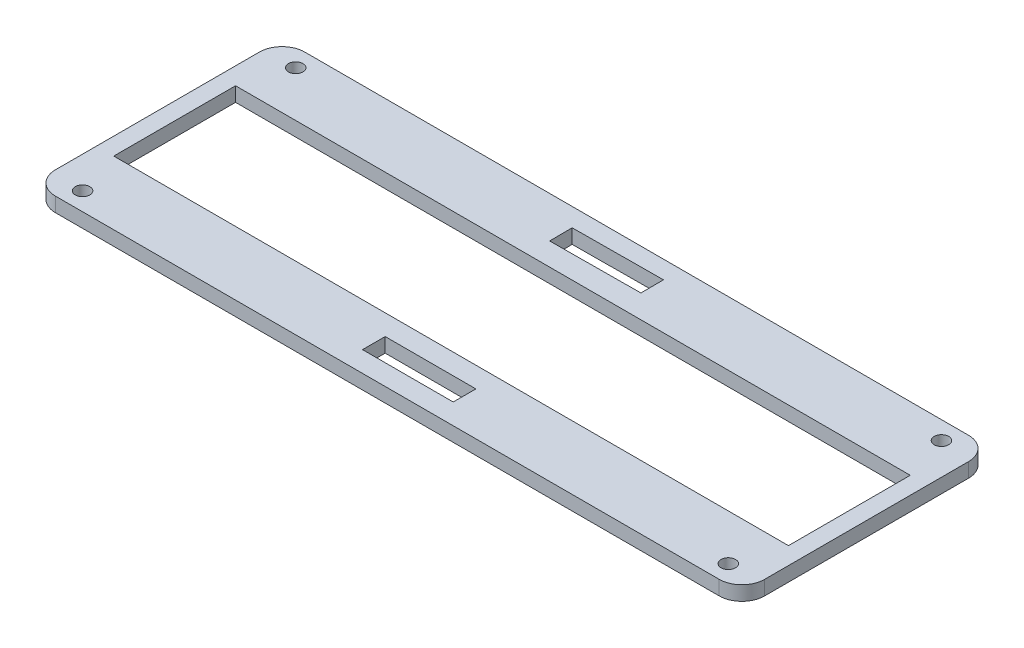
SolidWorks part; units mm, degrees
ref_plane "Front Plane" through (0, 0, 0) normal (0, 0, 1) x (1, 0, 0)
ref_plane "Top Plane" through (0, 0, 0) normal (0, 1, 0) x (1, 0, 0)
ref_plane "Right Plane" through (0, 0, 0) normal (1, 0, 0) x (0, 0, -1)
sketch "Sketch2" plane through (0, 0, 0) normal (0, 1, 0) x (1, 0, 0)
  line L1 (-78.2, 27.5) -> (78.2, 27.5)
  line L2 (-78.2, 27.5) -> (-78.2, -27.5)
  line L3 (-78.2, -27.5) -> (78.2, -27.5)
  line L4 (78.2, 27.5) -> (78.2, -27.5)
  line L5 (-78.2, 27.5) -> (78.2, -27.5) construction
  line L6 (-78.2, -27.5) -> (78.2, 27.5) construction
  point P0 (0, 0)
  dimension "D1" = 55
  dimension "D2" = 156.4
extrude "Boss-Extrude1" add sketch "Sketch2" along normal blind 3.175
ref_plane "Plane1" through (0, 0, 0) normal (0, 0, -1) x (-1, 0, 0)
sketch "Sketch3" plane through (0, 0, 0) normal (0, -1, 0) x (1, 0, 0)
  line L0 (72.39, 11.43) -> (72.39, -11.43) construction
  line L1 (-72.39, 11.43) -> (72.39, 11.43) construction
  line L2 (-72.39, 11.43) -> (-72.39, -11.43) construction
  line L3 (-72.39, -11.43) -> (72.39, -11.43) construction
  line L4 (72.39, 11.43) -> (72.39, -11.43) construction
  line L5 (-72.39, 11.43) -> (72.39, 11.43) construction
  line L6 (-72.39, 11.43) -> (-72.39, -11.43) construction
  line L7 (-72.39, -11.43) -> (72.39, -11.43) construction
  line L8 (-74.39, 13.43) -> (74.39, 13.43)
  line L9 (74.39, 13.43) -> (74.39, -13.43)
  line L10 (-74.39, -13.43) -> (74.39, -13.43)
  line L11 (-74.39, 13.43) -> (-74.39, -13.43)
  dimension "D1" = 2
extrude "Cut-Extrude1" cut sketch "Sketch3" against normal through all
sketch "Sketch4" plane through (0, 3.175, 0) normal (0, 1, 0) x (1, 0, 0)
  line L0 (-78.2, 0) -> (78.2, 0) construction
  line L1 (-78.2, -27.5) -> (-71.2, -27.5) construction
  line L2 (-78.2, -27.5) -> (-78.2, -23.5) construction
  line L3 (-78.2, -23.5) -> (-71.2, -23.5) construction
  line L4 (-71.2, -27.5) -> (-71.2, -23.5) construction
  line L5 (-78.2, -27.5) -> (-71.2, -23.5) construction
  line L6 (-78.2, -23.5) -> (-71.2, -27.5) construction
  line L7 (-78.2, 27.5) -> (-78.2, -27.5) construction
  line L8 (78.2, -27.5) -> (78.2, 27.5) construction
  line L9 (78.2, 0) -> (0, 0) construction
  line L10 (0, 0) -> (0, -27.5) construction
  line L11 (-78.2, -27.5) -> (78.2, -27.5) construction
  line L12 (0, -27.5) -> (0, 27.5) construction
  line L13 (78.2, 27.5) -> (-78.2, 27.5) construction
  circle A0 centre (-71.2, -23.5) radius 1.6
  circle A1 centre (-71.2, 23.5) radius 1.6
  circle A2 centre (71.2, 23.5) radius 1.6
  circle A3 centre (71.2, -23.5) radius 1.6
  point P4 (-74.7, -25.5)
  dimension "D3" = 3.2
  dimension "D1" = 7
  dimension "D2" = 4
extrude "Cut-Extrude2" cut sketch "Sketch4" against normal through all
sketch "Sketch5" plane through (0, 3.175, 0) normal (0, 1, 0) x (1, 0, 0)
  line L0 (0, -27.5) -> (0, -13.43) construction
  line L1 (-78.2, -27.5) -> (78.2, -27.5) construction
  line L2 (74.39, -13.43) -> (-74.39, -13.43) construction
  line L3 (78.2, 0.5219) -> (-78.2, 0) construction
  line L4 (-10, -22.965) -> (10, -22.965)
  line L5 (-10, -22.965) -> (-10, -17.965)
  line L6 (-10, -17.965) -> (10, -17.965)
  line L7 (10, -22.965) -> (10, -17.965)
  line L8 (-10, -22.965) -> (10, -17.965) construction
  line L9 (-10, -17.965) -> (10, -22.965) construction
  line L10 (78.2, -27.5) -> (78.2, 27.5) construction
  line L11 (-78.2, 27.5) -> (-78.2, -27.5) construction
  line L12 (-10.1548, 23.4197) -> (-10.1214, 18.4198)
  line L13 (-10.1548, 23.4197) -> (9.8448, 23.5532)
  line L14 (-10.1214, 18.4198) -> (9.8781, 18.5533)
  line L15 (9.8448, 23.5532) -> (9.8781, 18.5533)
  point P6 (0, -20.465)
  dimension "D1" = 5
  dimension "D2" = 20
extrude "Cut-Extrude3" cut sketch "Sketch5" against normal through all
fillet "Fillet1" radius 5 3 edges at (-78.2, 1.5875, 27.5) (-78.2, 1.5875, -27.5) (78.2, 1.5875, 27.5)
fillet "Fillet2" radius 5 1 edges at (78.2, 1.5875, -27.5)
